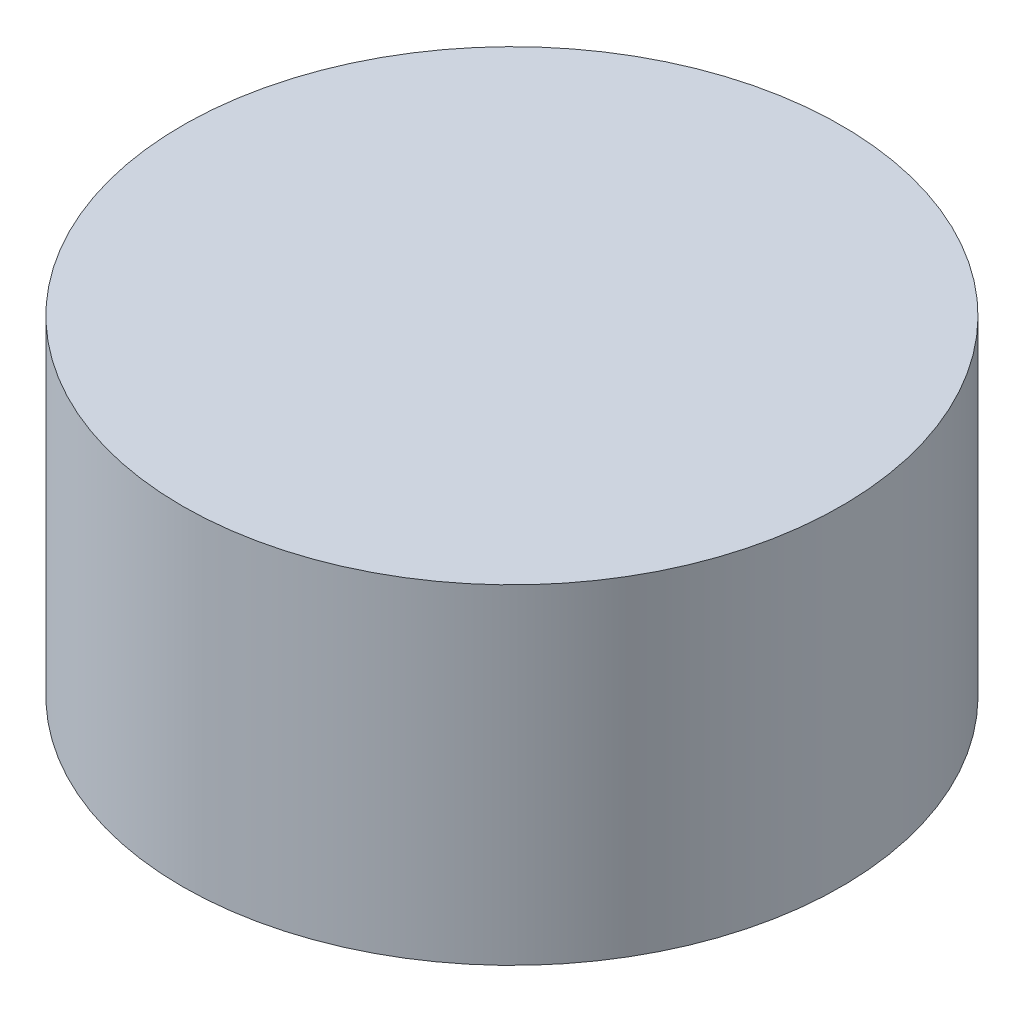
SolidWorks part; units mm, degrees
ref_plane "Front Plane" through (0, 0, 0) normal (0, 0, 1) x (1, 0, 0)
ref_plane "Top Plane" through (0, 0, 0) normal (0, 1, 0) x (1, 0, 0)
ref_plane "Right Plane" through (0, 0, 0) normal (1, 0, 0) x (0, 0, -1)
sketch "Sketch1" plane through (0, 0, 0) normal (0, 1, 0) x (1, 0, 0)
  circle A0 centre (0, 0) radius 0.3969
extrude "Boss-Extrude1" add sketch "Sketch1" along normal blind 0.3969
